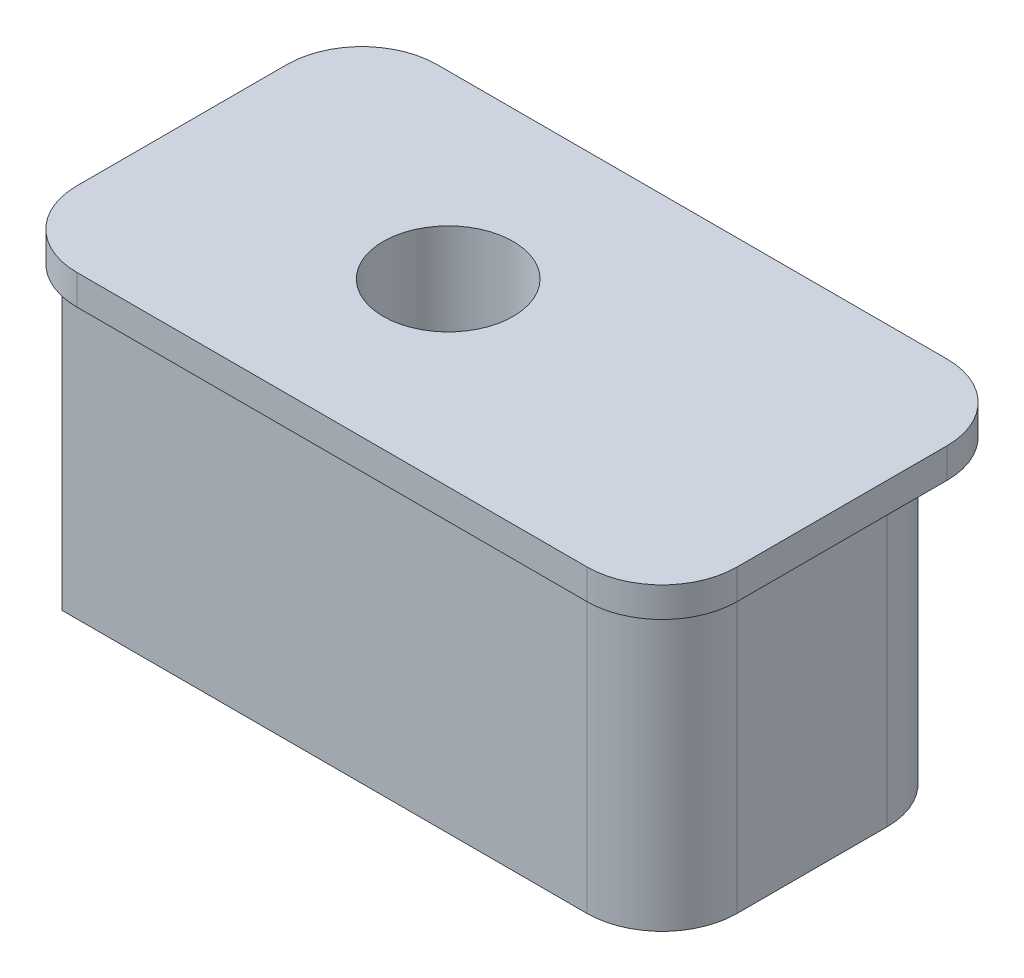
SolidWorks part; units mm, degrees
ref_plane "Front Plane" through (0, 0, 0) normal (0, 0, 1) x (1, 0, 0)
ref_plane "Top Plane" through (0, 0, 0) normal (0, 1, 0) x (1, 0, 0)
ref_plane "Right Plane" through (0, 0, 0) normal (1, 0, 0) x (0, 0, -1)
sketch "Sketch1" plane through (0, 0, 0) normal (0, 1, 0) x (1, 0, 0)
  line L1 (0, 0) -> (25.4, 0)
  line L2 (0, 0) -> (0, 12.7)
  line L3 (0, 12.7) -> (25.4, 12.7)
  line L4 (25.4, 0) -> (25.4, 12.7)
  dimension "D1" = 12.7
  dimension "D2" = 25.4
extrude "Boss-Extrude1" add sketch "Sketch1" along normal blind 12.7
fillet "Fillet1" radius 3.175 2 edges at (25.4, 6.35, -12.7) (25.4, 6.35, 0)
sketch "Sketch2" plane through (0, 12.7, 0) normal (0, 1, 0) x (1, 0, 0)
  line L0 (0, 12.7) -> (0, 0) construction
  line L1 (10, 12.7) -> (10, 6.35) construction
  line L2 (22.225, 12.7) -> (0, 12.7) construction
  line L3 (10, 6.35) -> (10, 0) construction
  line L4 (0, 0) -> (22.225, 0) construction
  circle A0 centre (10, 6.35) radius 2.75
  dimension "D2" = 5.5
  dimension "D1" = 10
extrude "Cut-Extrude1" cut sketch "Sketch2" against normal through all contours A0
sketch "Sketch3" plane through (0, 12.7, 0) normal (0, 1, 0) x (1, 0, 0)
  line L0 (22.225, 12.7) -> (0, 12.7) construction
  line L1 (-1.27, -1.27) -> (26.67, -1.27)
  line L2 (-1.27, -1.27) -> (-1.27, 13.97)
  line L3 (-1.27, 13.97) -> (26.67, 13.97)
  line L4 (26.67, -1.27) -> (26.67, 13.97)
  line L5 (0, 0) -> (22.225, 0) construction
  line L6 (0, 12.7) -> (0, 0) construction
  line L7 (25.4, 3.175) -> (25.4, 9.525) construction
  circle A0 centre (10, 6.35) radius 2.75 construction
  circle A1 centre (10, 6.35) radius 2.75
  dimension "D1" = 1.27
  dimension "D2" = 1.27
  dimension "D3" = 1.27
  dimension "D4" = 1.27
extrude "Boss-Extrude2" add sketch "Sketch3" along normal blind 1.27
fillet "Fillet2" radius 3.175 4 edges at (-1.27, 13.335, -13.97) (26.67, 13.335, -13.97) (26.67, 13.335, 1.27) (-1.27, 13.335, 1.27)
